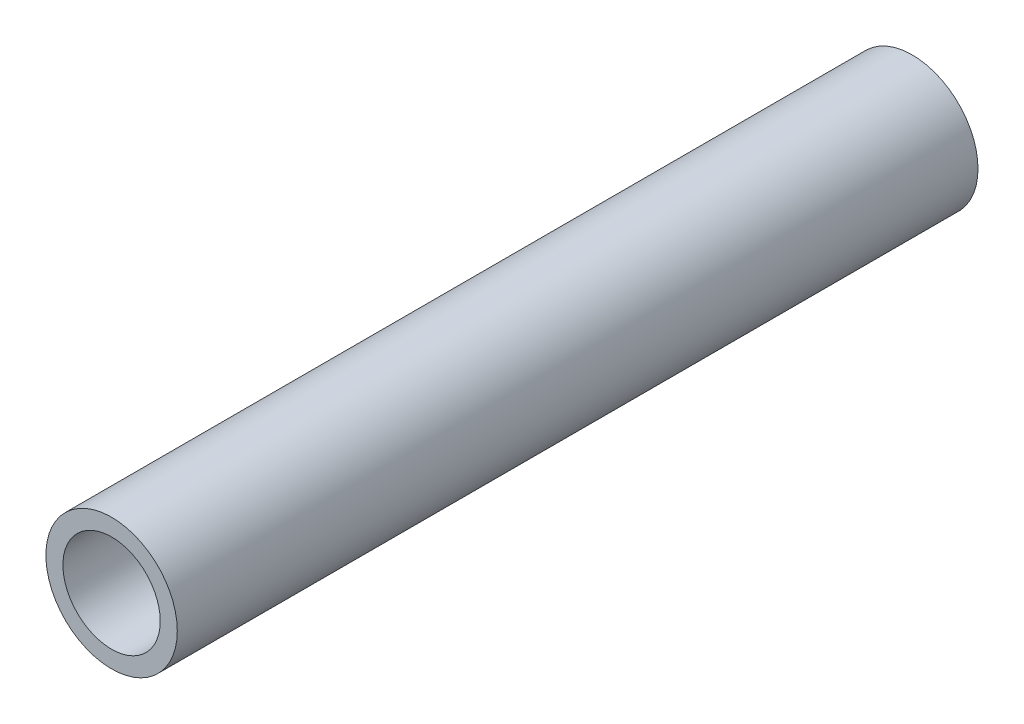
SolidWorks part; units mm, degrees
ref_plane "Front Plane" through (0, 0, 0) normal (0, 0, 1) x (1, 0, 0)
ref_plane "Top Plane" through (0, 0, 0) normal (0, 1, 0) x (1, 0, 0)
ref_plane "Right Plane" through (0, 0, 0) normal (1, 0, 0) x (0, 0, -1)
sketch "Sketch1" plane through (0, 0, 0) normal (0, 0, 1) x (1, 0, 0)
  circle A0 centre (0, 0) radius 10.668
  dimension "Pipe OD" = 21.336
extrude "Extrude-Thin1" add sketch "Sketch1" along normal mid plane 130 thin thin type one direction reverse wall 2.7686
